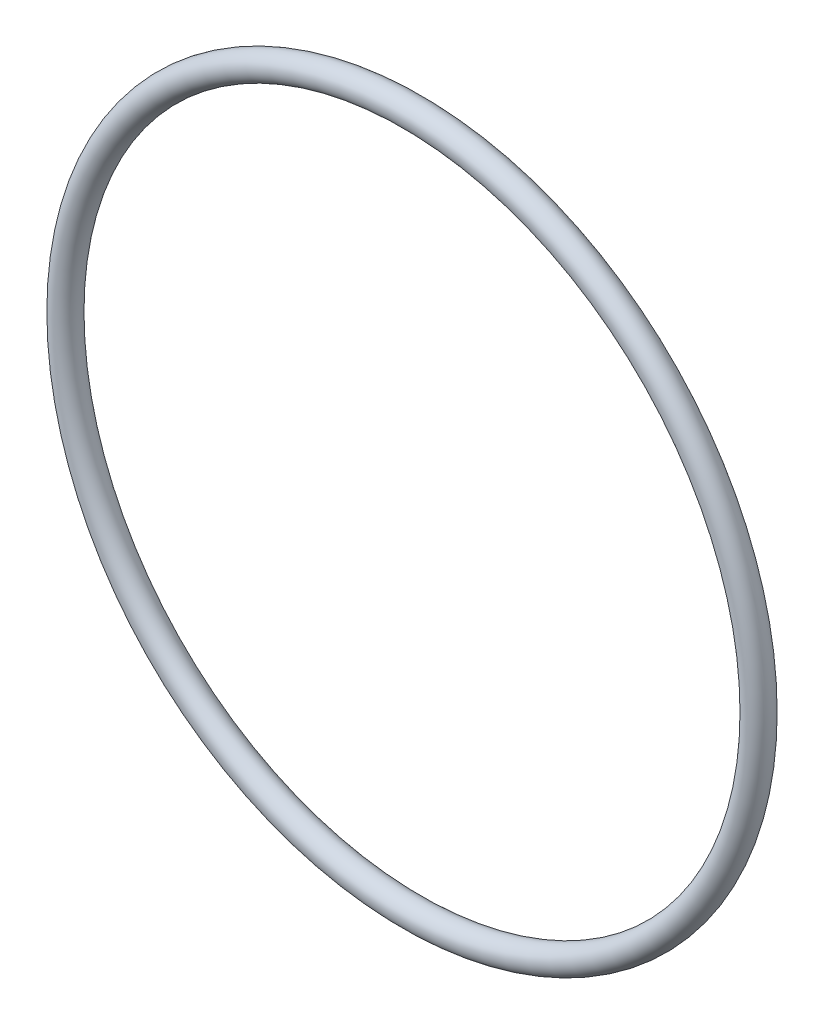
SolidWorks part; units mm, degrees
ref_plane "Front" through (0, 0, 0) normal (0, 0, 1) x (1, 0, 0)
ref_plane "Top" through (0, 0, 0) normal (0, 1, 0) x (1, 0, 0)
ref_plane "Right" through (0, 0, 0) normal (1, 0, 0) x (0, 0, -1)
sketch "Sketch1" plane through (0, 0, 0) normal (1, 0, 0) x (0, -1, 0)
  line L0 (0, -3.4925) -> (0, 3.4925) construction
  line L2 (-105.1242, 0) -> (105.1242, 0) construction
  line L3 (-88.5825, 0) -> (88.5825, 0) construction
  circle A0 centre (92.075, 0) radius 3.4925
  point P9 (88.5825, 0)
  point P10 (95.5675, 0)
  point P13 (92.075, 3.4925)
  point P14 (92.075, -3.4925)
  dimension "Width" = 6.985
  dimension "ID" = 177.165
revolve "Revolve1" add sketch "Sketch1" angle 360 about L0
